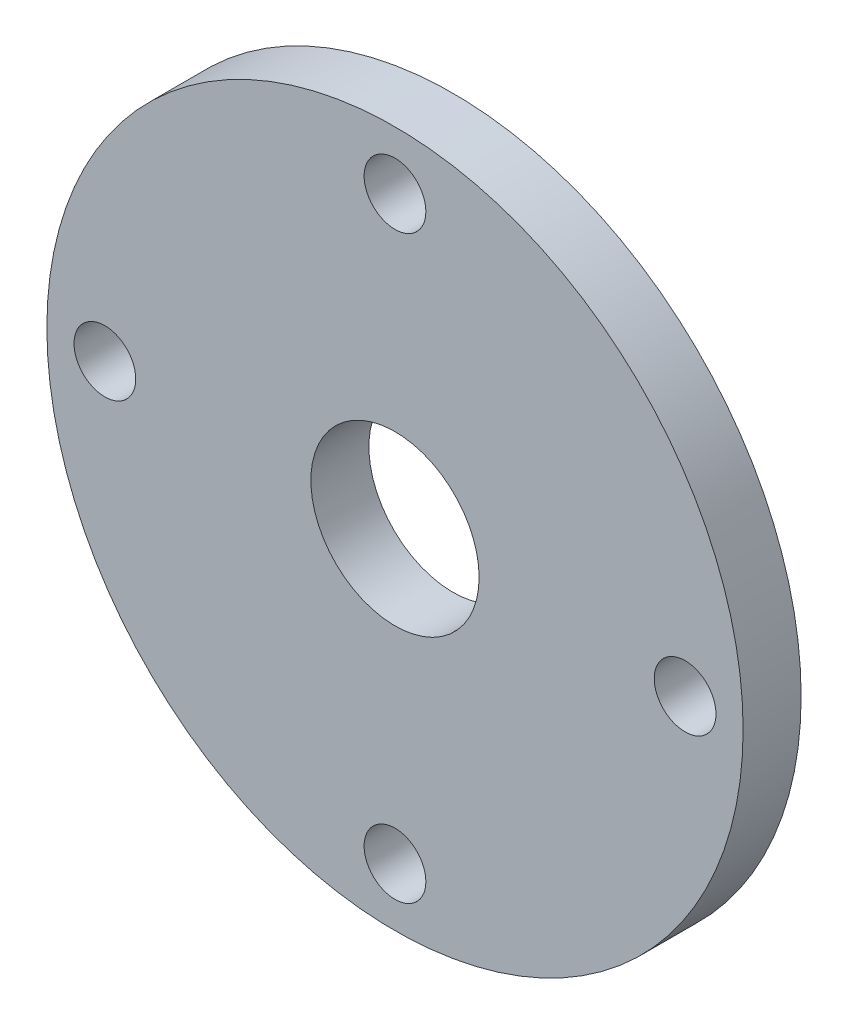
SolidWorks part; units mm, degrees
ref_plane "Front Plane" through (0, 0, 0) normal (0, 0, 1) x (1, 0, 0)
ref_plane "Top Plane" through (0, 0, 0) normal (0, 1, 0) x (1, 0, 0)
ref_plane "Right Plane" through (0, 0, 0) normal (1, 0, 0) x (0, 0, -1)
sketch "Sketch1" plane through (0, 0, 0) normal (0, 0, 1) x (1, 0, 0)
  circle A0 centre (0, 0) radius 38.1
  dimension "D1" = 76.2
extrude "Boss-Extrude1" add sketch "Sketch1" along normal blind 6.35
sketch "Sketch2" plane through (0, 0, 6.35) normal (0, 0, 1) x (1, 0, 0)
  line L0 (0, 0) -> (0, 31.75) construction
  circle A0 centre (0, 0) radius 31.75 construction
  circle A1 centre (0, 31.75) radius 3.3782
  circle A2 centre (31.75, 0) radius 3.3782
  circle A3 centre (0, -31.75) radius 3.3782
  circle A4 centre (-31.75, 0) radius 3.3782
  point P5 (4.609, -37.8202)
  point P6 (0, 0)
  point P14 (0, 0)
  point P15 (0, 0)
  point P16 (-22.7638, -30.5519)
  dimension "D1" = 63.5
  dimension "D2" = 6.7564
  dimension "D3" = 4
extrude "Cut-Extrude1" cut sketch "Sketch2" against normal blind 6.35
sketch "Sketch3" plane through (0, 0, 6.35) normal (0, 0, 1) x (1, 0, 0)
  circle A0 centre (0, 0) radius 9.2075
  dimension "D1" = 18.415
extrude "Cut-Extrude2" cut sketch "Sketch3" against normal blind 6.35
